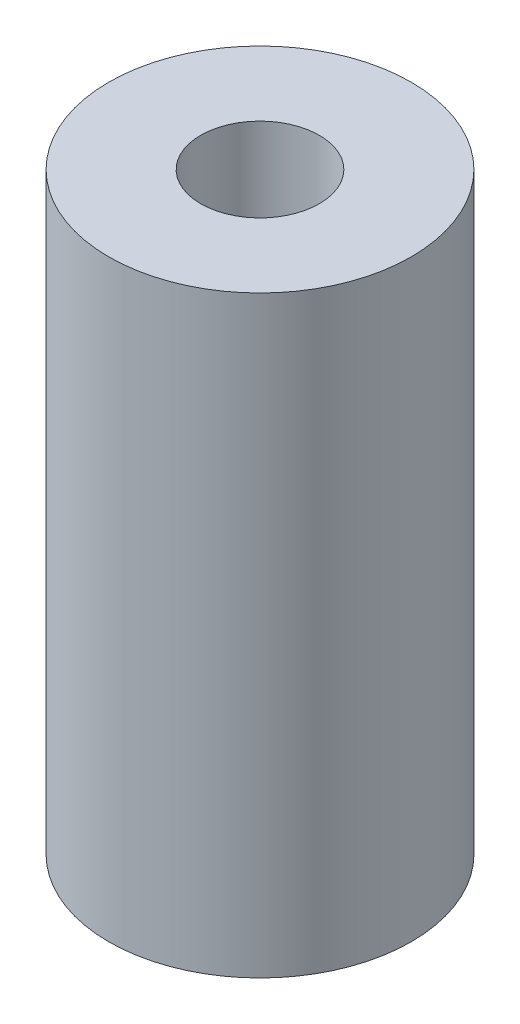
SolidWorks part; units mm, degrees
material "KNSB"
ref_plane "정면" through (0, 0, 0) normal (0, 0, 1) x (1, 0, 0)
ref_plane "윗면" through (0, 0, 0) normal (0, 1, 0) x (1, 0, 0)
ref_plane "우측면" through (0, 0, 0) normal (1, 0, 0) x (0, 0, -1)
sketch "스케치1" plane through (0, 0, 0) normal (0, 1, 0) x (1, 0, 0)
  circle A0 centre (0, 0) radius 25.5
  circle A1 centre (0, 0) radius 10
  dimension "D1" = 51
  dimension "D2" = 20
extrude "보스-돌출1" add sketch "스케치1" along normal blind 100
